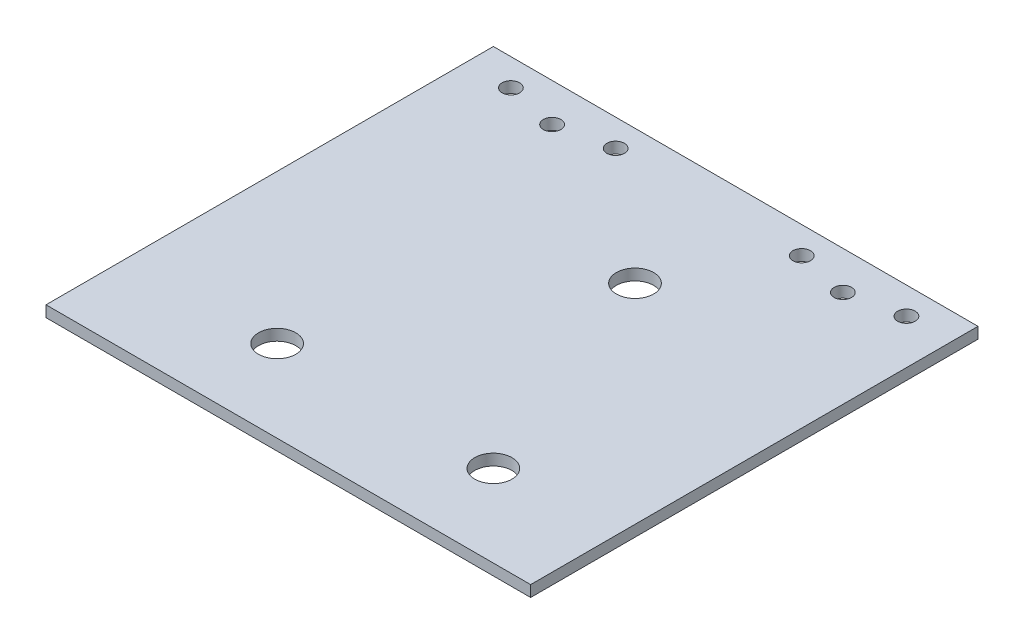
SolidWorks part; units mm, degrees
ref_plane "Front Plane" through (0, 0, 0) normal (0, 0, 1) x (1, 0, 0)
ref_plane "Top Plane" through (0, 0, 0) normal (0, 1, 0) x (1, 0, 0)
ref_plane "Right Plane" through (0, 0, 0) normal (1, 0, 0) x (0, 0, -1)
sketch "Sketch1" plane through (0, 0, 0) normal (0, 1, 0) x (1, 0, 0)
  line L1 (0, 0) -> (130, 0)
  line L2 (0, 0) -> (0, -150)
  line L3 (0, -150) -> (130, -150)
  line L4 (130, 0) -> (130, -150)
  dimension "D1" = 130
  dimension "D2" = 150
extrude "Boss-Extrude1" add sketch "Sketch1" along normal blind 3
hole_wizard "Ø10.0 (10) Diameter Hole2" positions "Sketch3" profile "Sketch2" hole size "Ø10.0" standard "ANSI Metric" end condition through all
sketch "Sketch3" plane through (0, 3, 0) normal (0, 1, 0) x (1, 0, 0)
  point P16 (40, -128)
  point P18 (98, -128)
  point P20 (74, -66)
sketch "Sketch2" plane through (40, 3, 128) normal (1, 0, 0) x (0, 0, 1)
  line L0 (0, 0) -> (0, 3)
  line L1 (0, 3) -> (5, 3)
  line L2 (5, 3) -> (5, 0)
  line L5 (5, 0) -> (0, 0)
  line L11 (0, -6.35) -> (0, 107.95) construction
  dimension "Thru Hole Dia." = 10
  dimension "Thru Hole Depth" = 3
sketch "Sketch4" plane through (0, 0, 0) normal (0, 1, 0) x (1, 0, 0)
  line L0 (4.6863, -27.3137) -> (27.3137, -4.6863) construction
  line L1 (4.6863, -4.6863) -> (27.3137, -4.6863) construction
  line L2 (4.6863, -4.6863) -> (4.6863, -27.3137) construction
  line L3 (4.6863, -27.3137) -> (27.3137, -27.3137) construction
  line L4 (27.3137, -4.6863) -> (27.3137, -27.3137) construction
  line L5 (4.6863, -4.6863) -> (27.3137, -27.3137) construction
  line L6 (130, 0) -> (0, 0) construction
  line L7 (0, 0) -> (0, -150) construction
  line L8 (130, -150) -> (130, 0) construction
  line L9 (102.6863, -4.6863) -> (125.3137, -4.6863) construction
  line L10 (102.6863, -4.6863) -> (102.6863, -27.3137) construction
  line L11 (102.6863, -27.3137) -> (125.3137, -27.3137) construction
  line L12 (125.3137, -4.6863) -> (125.3137, -27.3137) construction
  line L13 (102.6863, -4.6863) -> (125.3137, -27.3137) construction
  line L14 (102.6863, -27.3137) -> (125.3137, -4.6863) construction
  line L15 (16, -16) -> (114, -16) construction
  line L17 (53.6863, -4.6863) -> (76.3137, -4.6863) construction
  line L18 (53.6863, -4.6863) -> (53.6863, -27.3137) construction
  line L19 (53.6863, -27.3137) -> (76.3137, -27.3137) construction
  line L20 (76.3137, -4.6863) -> (76.3137, -27.3137) construction
  line L21 (53.6863, -4.6863) -> (76.3137, -27.3137) construction
  line L22 (53.6863, -27.3137) -> (76.3137, -4.6863) construction
  circle A0 centre (16, -16) radius 16 construction
  circle A1 centre (65, -16) radius 16 construction
  circle A2 centre (114, -16) radius 16 construction
  point P10 (114, -16)
  dimension "D2" = 32
  dimension "D3" = 32
  dimension "D1" = 32
hole_wizard "Ø14.0 (14) Diameter Hole1" positions "Sketch6" profile "Sketch5" hole size "Ø14.0" standard "ANSI Metric" end condition through all
sketch "Sketch6" plane through (0, 3, 0) normal (0, 1, 0) x (1, 0, 0)
  point P0 (16, -16)
  point P2 (114, -16)
sketch "Sketch5" plane through (16, 3, 16) normal (1, 0, 0) x (0, 0, 1)
  line L0 (0, 0) -> (0, 3)
  line L1 (0, 3) -> (7, 3)
  line L2 (7, 3) -> (7, 0)
  line L5 (7, 0) -> (0, 0)
  line L11 (0, -6.35) -> (0, 107.95) construction
  dimension "Thru Hole Dia." = 14
  dimension "Thru Hole Depth" = 3
hole_wizard "Ø5.0 (5) Diameter Hole1" positions "Sketch8" profile "Sketch7" hole size "Ø5.0" standard "ANSI Metric" end condition through all
sketch "Sketch8" plane through (0, 3, 0) normal (0, 1, 0) x (1, 0, 0)
  point P0 (4.6863, -27.3137)
  point P2 (4.6863, -4.6863)
  point P4 (27.3137, -4.6863)
  point P6 (27.3137, -27.3137)
  point P8 (102.6863, -27.3137)
  point P10 (125.3137, -27.3137)
  point P12 (125.3137, -4.6863)
  point P14 (102.6863, -4.6863)
sketch "Sketch7" plane through (4.6863, 3, 27.3137) normal (1, 0, 0) x (0, 0, 1)
  line L0 (0, 0) -> (0, 3)
  line L1 (0, 3) -> (2.5, 3)
  line L2 (2.5, 3) -> (2.5, 0)
  line L5 (2.5, 0) -> (0, 0)
  line L11 (0, -6.35) -> (0, 107.95) construction
  dimension "Thru Hole Dia." = 5
  dimension "Thru Hole Depth" = 3
hole_wizard "Ø9.0 (9) Diameter Hole1" positions "Sketch12" profile "Sketch11" hole size "Ø9.0" standard "ANSI Metric" end condition through all
sketch "Sketch12" plane through (0, 3, 0) normal (0, 1, 0) x (1, 0, 0)
  point P5 (65, -16)
sketch "Sketch11" plane through (65, 3, 16) normal (1, 0, 0) x (0, 0, 1)
  line L0 (0, 0) -> (0, 3)
  line L1 (0, 3) -> (4.5, 3)
  line L2 (4.5, 3) -> (4.5, 0)
  line L5 (4.5, 0) -> (0, 0)
  line L11 (0, -6.35) -> (0, 107.95) construction
  dimension "Thru Hole Dia." = 9
  dimension "Thru Hole Depth" = 3
hole_wizard "Ø5.0 (5) Diameter Hole2" positions "Sketch14" profile "Sketch13" hole size "Ø5.0" standard "ANSI Metric" end condition through all
sketch "Sketch14" plane through (0, 3, 0) normal (0, 1, 0) x (1, 0, 0)
  point P0 (53.6863, -27.3137)
  point P2 (76.3137, -27.3137)
  point P4 (76.3137, -4.6863)
  point P6 (53.6863, -4.6863)
sketch "Sketch13" plane through (53.6863, 3, 27.3137) normal (1, 0, 0) x (0, 0, 1)
  line L0 (0, 0) -> (0, 3)
  line L1 (0, 3) -> (2.5, 3)
  line L2 (2.5, 3) -> (2.5, 0)
  line L5 (2.5, 0) -> (0, 0)
  line L11 (0, -6.35) -> (0, 107.95) construction
  dimension "Thru Hole Dia." = 5
  dimension "Thru Hole Depth" = 3
sketch "Sketch15" plane through (0, 0, 0) normal (0, 1, 0) x (1, 0, 0)
  line L0 (130, -150) -> (130, 0) construction
  line L1 (0, 0) -> (130, 0)
  line L2 (0, 0) -> (0, -30)
  line L3 (0, -30) -> (130, -30)
  line L4 (130, 0) -> (130, -30)
  line L5 (0, -150) -> (130, -150) construction
  dimension "D1" = 120
extrude "Cut-Extrude1" cut sketch "Sketch15" along normal through all
sketch "Sketch16" plane through (0, 0, 0) normal (0, 1, 0) x (1, 0, 0)
  line L0 (104, -40.25) -> (104, -37.25) construction
  line L1 (118.05, -37.25) -> (89.95, -37.25) construction
  line L2 (0, -30) -> (130, -30) construction
  line L3 (130, -150) -> (130, -30) construction
  line L4 (26, -40.25) -> (26, -37.25) construction
  line L5 (40.05, -37.25) -> (11.95, -37.25) construction
  circle A0 centre (89.95, -37.25) radius 2.35
  circle A1 centre (118.05, -37.25) radius 2.35
  circle A2 centre (104, -40.25) radius 2.35
  circle A3 centre (11.95, -37.25) radius 2.35
  circle A4 centre (40.05, -37.25) radius 2.35
  circle A5 centre (26, -40.25) radius 2.35
  dimension "D4" = 4.7
  dimension "D1" = 28.1
  dimension "D2" = 10.25
  dimension "D3" = 3
  dimension "D5" = 26
  dimension "D6" = 28.1
  dimension "D7" = 78
extrude "Cut-Extrude2" cut sketch "Sketch16" along normal through all
equation "\"a\"= 130"
equation "\"b\"= 150"
equation "\"D2@Sketch1\"=\"b\""
equation "\"D1@Sketch1\"=\"a\""
